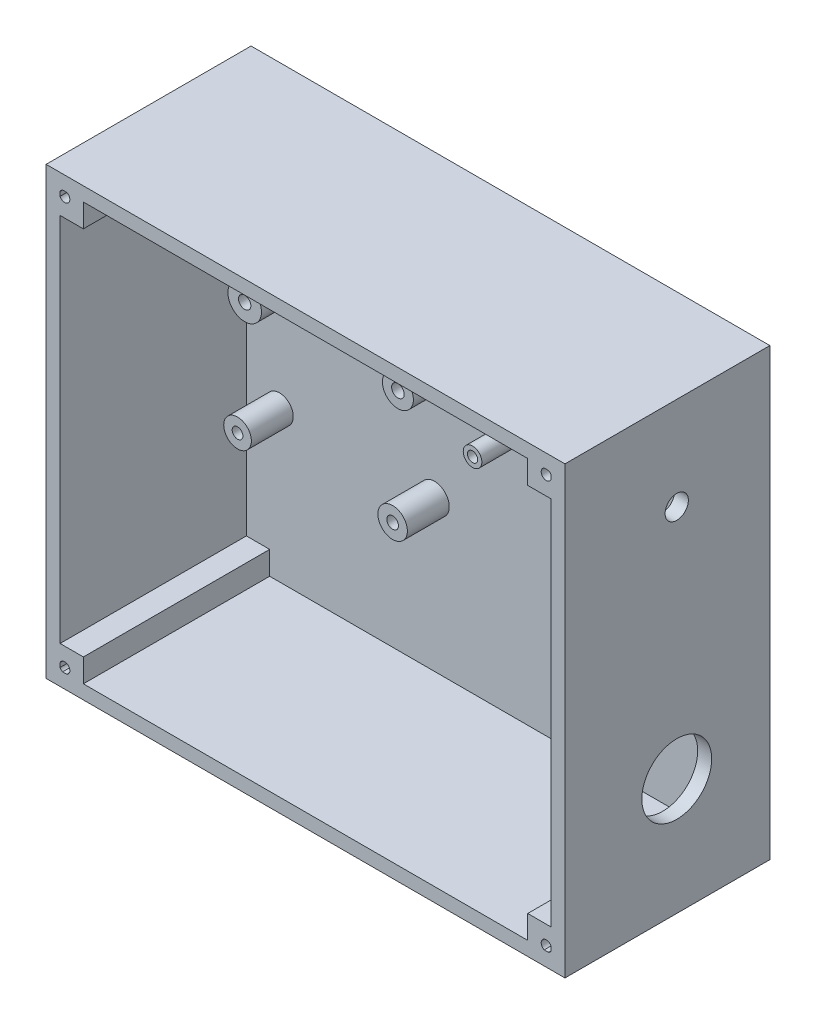
SolidWorks part; units mm, degrees
ref_plane "Front Plane" through (0, 0, 0) normal (0, 0, 1) x (1, 0, 0)
ref_plane "Top Plane" through (0, 0, 0) normal (0, 1, 0) x (1, 0, 0)
ref_plane "Right Plane" through (0, 0, 0) normal (1, 0, 0) x (0, 0, -1)
sketch "Sketch1" plane through (0, 0, 0) normal (0, 0, 1) x (1, 0, 0)
  line L1 (0, 0) -> (141.478, 0)
  line L2 (0, 0) -> (0, 121.412)
  line L3 (0, 121.412) -> (141.478, 121.412)
  line L4 (141.478, 0) -> (141.478, 121.412)
  dimension "D1" = 141.478
  dimension "D2" = 121.412
extrude "Boss-Extrude1" add sketch "Sketch1" along normal blind 5.08
sketch "Sketch2" plane through (0, 0, 5.08) normal (0, 0, 1) x (1, 0, 0)
  line L0 (141.478, 121.412) -> (0, 121.412) construction
  line L1 (3.81, 117.602) -> (137.668, 117.602)
  line L2 (3.81, 117.602) -> (3.81, 3.81)
  line L3 (3.81, 3.81) -> (137.668, 3.81)
  line L4 (137.668, 117.602) -> (137.668, 3.81)
  line L5 (0, 121.412) -> (0, 0) construction
  line L6 (0, 0) -> (141.478, 0) construction
  line L7 (141.478, 0) -> (141.478, 121.412) construction
  line L9 (0, 121.412) -> (141.478, 121.412)
  line L10 (0, 121.412) -> (0, 0)
  line L11 (0, 0) -> (141.478, 0)
  line L12 (141.478, 121.412) -> (141.478, 0)
  dimension "D1" = 3.81
  dimension "D2" = 3.81
  dimension "D3" = 3.81
  dimension "D4" = 3.81
extrude "Boss-Extrude2" add sketch "Sketch2" along normal blind 50.8
sketch "Sketch3" plane through (0, 0, 5.08) normal (0, 0, 1) x (1, 0, 0)
  line L1 (0, 121.412) -> (10.16, 121.412)
  line L2 (0, 121.412) -> (0, 111.252)
  line L3 (0, 111.252) -> (10.16, 111.252)
  line L4 (10.16, 121.412) -> (10.16, 111.252)
  line L5 (0, 0) -> (10.16, 0)
  line L6 (0, 0) -> (0, 10.16)
  line L7 (0, 10.16) -> (10.16, 10.16)
  line L8 (10.16, 0) -> (10.16, 10.16)
  line L9 (141.478, 0) -> (131.318, 0)
  line L10 (141.478, 0) -> (141.478, 10.16)
  line L11 (141.478, 10.16) -> (131.318, 10.16)
  line L12 (131.318, 0) -> (131.318, 10.16)
  line L13 (141.478, 121.412) -> (131.318, 121.412)
  line L14 (141.478, 121.412) -> (141.478, 111.252)
  line L15 (141.478, 111.252) -> (131.318, 111.252)
  line L16 (131.318, 121.412) -> (131.318, 111.252)
  circle A0 centre (136.398, 116.332) radius 1.397
  circle A1 centre (136.398, 5.08) radius 1.397
  circle A2 centre (5.08, 5.08) radius 1.397
  circle A3 centre (5.08, 116.332) radius 1.397
  dimension "D3" = 2.794
  dimension "D4" = 5.08
  dimension "D5" = 5.08
  dimension "D8" = 5.08
  dimension "D9" = 5.08
  dimension "D10" = 2.794
  dimension "D13" = 5.08
  dimension "D14" = 5.08
  dimension "D15" = 2.794
  dimension "D18" = 2.794
  dimension "D19" = 5.08
  dimension "D20" = 5.08
  dimension "D1" = 10.16
  dimension "D2" = 10.16
  dimension "D6" = 10.16
  dimension "D7" = 10.16
  dimension "D11" = 10.16
  dimension "D12" = 10.16
  dimension "D16" = 10.16
  dimension "D17" = 10.16
extrude "Boss-Extrude3" add sketch "Sketch3" along normal blind 50.8
sketch "Sketch4" plane through (141.478, 0, 0) normal (1, 0, 0) x (0, 0, -1)
  line L0 (0, 0) -> (0, 121.412) construction
  line L1 (-55.88, 0) -> (0, 0) construction
  circle A0 centre (-25.4, 31.75) radius 9.525
  dimension "D1" = 19.05
  dimension "D2" = 25.4
  dimension "D3" = 31.75
extrude "Cut-Extrude1" cut sketch "Sketch4" against normal blind 50.8
sketch "Sketch5" plane through (141.478, 0, 0) normal (1, 0, 0) x (0, 0, -1)
  line L0 (-55.88, 121.412) -> (0, 121.412) construction
  line L1 (0, 0) -> (0, 121.412) construction
  circle A0 centre (-25.4, 96.012) radius 3.175
  dimension "D1" = 6.35
  dimension "D2" = 25.4
  dimension "D3" = 25.4
extrude "Cut-Extrude2" cut sketch "Sketch5" against normal blind 50.8
sketch "Sketch6" plane through (0, 0, 5.08) normal (0, 0, 1) x (1, 0, 0)
  line L0 (118.3136, 111.7698) -> (73.8636, 111.7698) construction
  line L1 (73.8636, 111.7698) -> (73.8636, 67.3198) construction
  line L2 (118.3136, 67.3198) -> (118.3136, 111.7698) construction
  line L3 (73.8636, 67.3198) -> (118.3136, 67.3198) construction
  circle A0 centre (56.5552, 108.1567) radius 1.7421
  circle A1 centre (56.5552, 108.1567) radius 5.3525
  circle A2 centre (56.5552, 76.5337) radius 1.7145
  circle A3 centre (56.5552, 76.5337) radius 4.2224
  circle A4 centre (14.7722, 76.5337) radius 1.684
  circle A5 centre (14.7722, 76.5337) radius 4.5798
  circle A6 centre (14.7722, 108.1567) radius 1.7319
  circle A7 centre (14.7722, 108.1567) radius 3.9883
  circle A8 centre (55.117, 44.699) radius 1.5886
  circle A9 centre (55.117, 44.699) radius 4.0156
  circle A10 centre (12.826, 44.699) radius 1.461
  circle A11 centre (12.826, 44.699) radius 3.7682
  circle A12 centre (114.5036, 107.9598) radius 2.921
  circle A13 centre (114.5036, 107.9598) radius 1.397
  circle A14 centre (76.9116, 71.1298) radius 2.54
  circle A15 centre (76.9116, 71.1298) radius 1.397
  circle A16 centre (77.6736, 107.9598) radius 2.921
  circle A17 centre (77.6736, 107.9598) radius 1.397
  dimension "D1" = 3.81
  dimension "D2" = 3.81
  dimension "D3" = 2.794
  dimension "D4" = 5.842
  dimension "D5" = 2.794
  dimension "D6" = 5.842
  dimension "D7" = 3.81
  dimension "D8" = 3.81
  dimension "D9" = 2.794
  dimension "D10" = 5.08
  dimension "D11" = 3.048
  dimension "D12" = 3.81
extrude "Boss-Extrude4" add sketch "Sketch6" along normal blind 11.43
